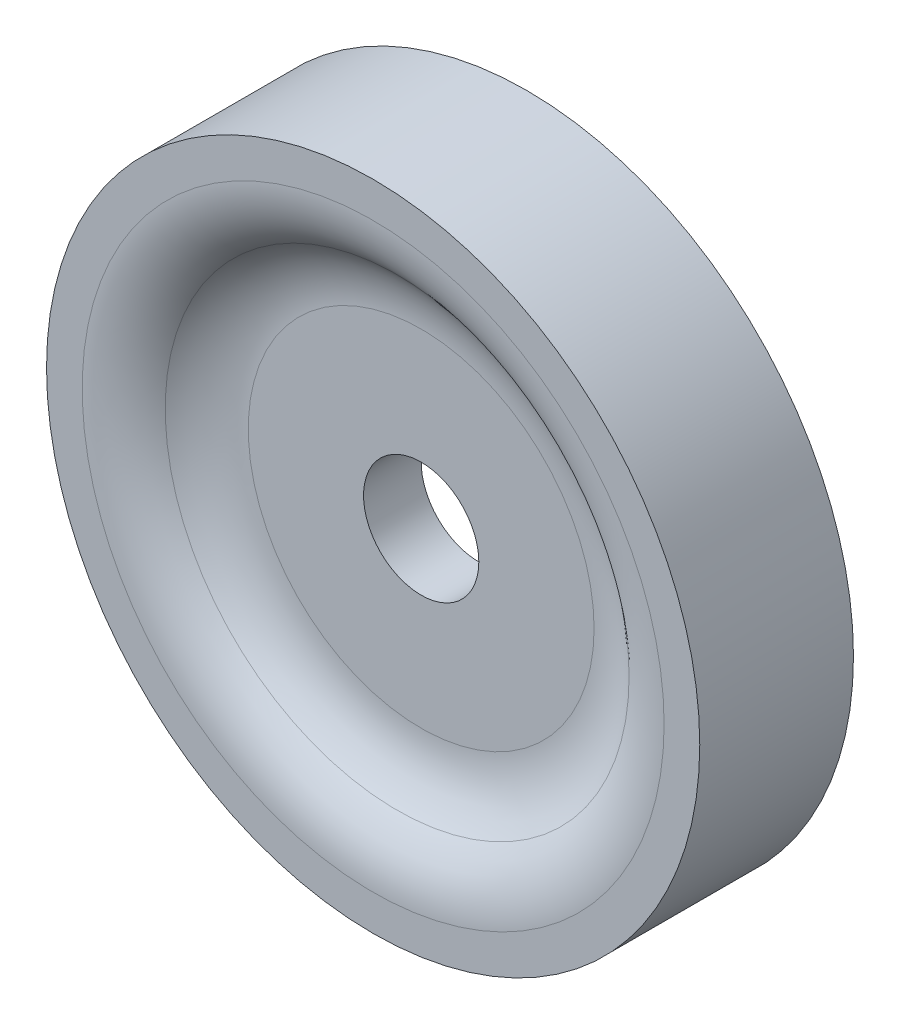
SolidWorks part; units mm, degrees
ref_plane "Alzado" through (0, 0, 0) normal (0, 0, 1) x (1, 0, 0)
ref_plane "Planta" through (0, 0, 0) normal (0, 1, 0) x (1, 0, 0)
ref_plane "Vista lateral" through (0, 0, 0) normal (1, 0, 0) x (0, 0, -1)
sketch "Croquis2" plane through (0, 0, 0) normal (0, 1, 0) x (1, 0, 0)
  line L0 (15, -7.5) -> (15, 7.5)
  line L1 (15, 7.5) -> (45, 7.5)
  line L2 (75.7205, 20) -> (85, 20)
  line L3 (85, 20) -> (85, -20)
  line L4 (15, 0) -> (47.3385, 0) construction
  line L5 (75.7205, -20) -> (85, -20)
  line L6 (15, -7.5) -> (45, -7.5)
  line L7 (0, 0) -> (0, 24.0728) construction
  arc A0 (45, 7.5) -> (60.3603, 13.75) centre (45, 29.5) ccw
  arc A1 (60.3603, 13.75) -> (75.7205, 20) centre (75.7205, -2) cw
  arc A2 (60.3603, -13.75) -> (75.7205, -20) centre (75.7205, 2) ccw
  arc A3 (45, -7.5) -> (60.3603, -13.75) centre (45, -29.5) cw
  point P10 (85, 0)
  point P20 (55, 7.5)
  dimension "D5" = 22
  dimension "D1" = 15
  dimension "D2" = 20
  dimension "D3" = 7.5
  dimension "D4" = 30
  dimension "D6" = 85
revolve "Revolución1" add sketch "Croquis2" angle 360 about L7
